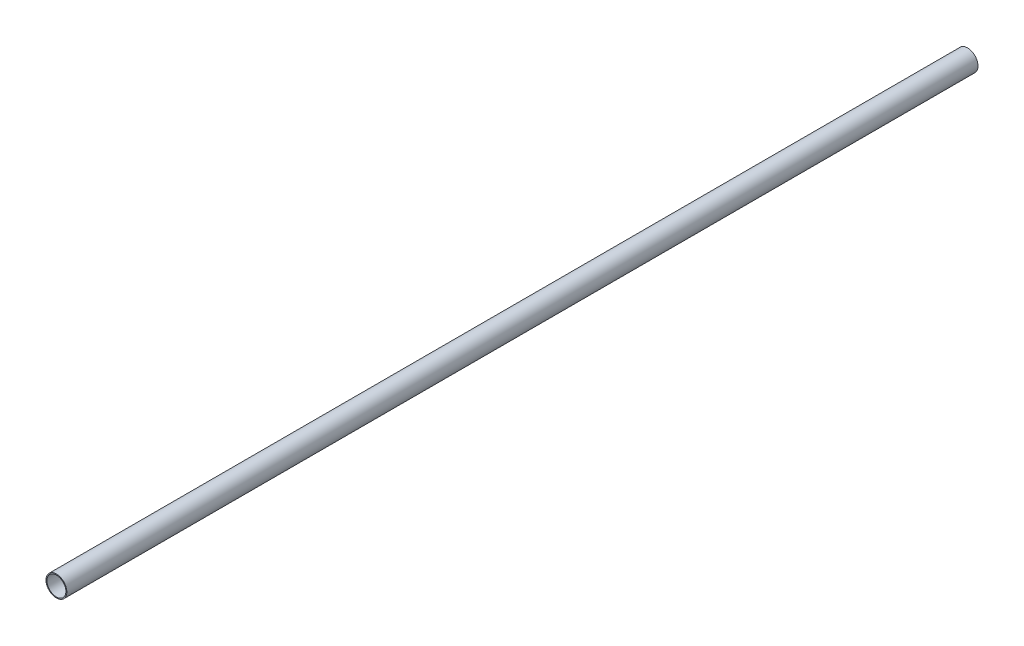
SolidWorks part; units mm, degrees
material "Carbon Fiber Tube - UD Approx"
ref_plane "Front Plane" through (0, 0, 0) normal (0, 0, 1) x (1, 0, 0)
ref_plane "Top Plane" through (0, 0, 0) normal (0, 1, 0) x (1, 0, 0)
ref_plane "Right Plane" through (0, 0, 0) normal (1, 0, 0) x (0, 0, -1)
sketch "Sketch1" plane through (0, 0, 0) normal (0, 0, 1) x (1, 0, 0)
  circle A0 centre (0, 0) radius 11
  circle A1 centre (0, 0) radius 10
  dimension "D1" = 22
  dimension "D2" = 20
extrude "Boss-Extrude1" add sketch "Sketch1" along normal blind 961
